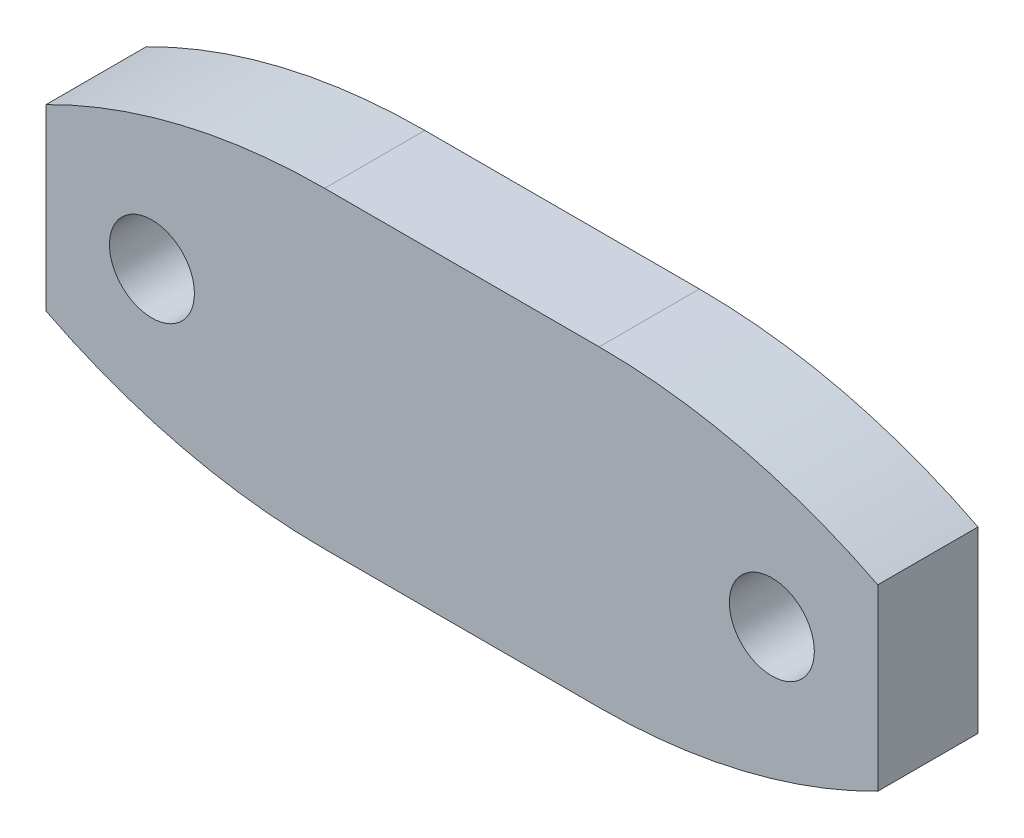
SolidWorks part; units mm, degrees
ref_plane "Front Plane" through (0, 0, 0) normal (0, 0, 1) x (1, 0, 0)
ref_plane "Top Plane" through (0, 0, 0) normal (0, 1, 0) x (1, 0, 0)
ref_plane "Right Plane" through (0, 0, 0) normal (1, 0, 0) x (0, 0, -1)
sketch "Sketch1" plane through (0, 0, 0) normal (0, 0, 1) x (1, 0, 0)
  line L1 (0, 0) -> (63.9, 0)
  line L2 (0, 0) -> (0, 24)
  line L3 (0, 24) -> (63.9, 24)
  line L4 (63.9, 0) -> (63.9, 24)
  dimension "D1" = 63.9
  dimension "D2" = 24
extrude "Boss-Extrude1" add sketch "Sketch1" along normal blind 7.7
sketch "Sketch2" plane through (0, 0, 7.7) normal (0, 0, 1) x (1, 0, 0)
  line L0 (31.95, 12) -> (55.7625, 12) construction
  line L1 (31.95, 24) -> (31.95, 0) construction
  line L2 (63.9, 24) -> (0, 24) construction
  line L3 (0, 0) -> (63.9, 0) construction
  line L4 (31.95, 12) -> (8.1375, 12) construction
  dimension "D1" = 47.625
hole_wizard "5/16-18 Tapped Hole1" positions "3DSketch1" profile "Sketch3" tap size "5/16-18" standard "ANSI Inch" end condition through all
sketch3d "3DSketch1"
  point P0 (8.1375, 12, 7.7)
  point P3 (55.7625, 12, 7.7)
sketch "Sketch3" plane through (8.1375, 12, 7.7) normal (1, 0, 0) x (0, -1, 0)
  line L0 (0, 0) -> (0, 7.7)
  line L1 (0, 7.7) -> (3.2639, 7.7)
  line L2 (3.2639, 7.7) -> (3.2639, 0)
  line L5 (3.2639, 0) -> (0, 0)
  line L11 (0, -6.35) -> (0, 107.95) construction
  dimension "Thru Tap Drill Dia." = 6.5278
  dimension "Thru Tap Drill Depth" = 7.7
cosmetic thread "Hole Thread1" parameters "D2"=7.9375
cosmetic thread "Hole Thread2" parameters "D2"=7.9375
sketch "Sketch4" plane through (0, 0, 7.7) normal (0, 0, 1) x (1, 0, 0)
  line L0 (63.9, 24) -> (63.9, 18.8676)
  line L1 (0, 24) -> (0, 0) construction
  line L2 (31.95, 12) -> (8.1375, 12) construction
  line L3 (31.95, 12) -> (55.7625, 12) construction
  line L4 (31.95, 24) -> (31.95, 0) construction
  line L5 (31.95, 12) -> (8.1375, 12) construction
  line L6 (31.95, 12) -> (55.7625, 12) construction
  line L7 (31.95, 24) -> (31.95, 0) construction
  line L12 (21.4029, 24) -> (0, 24)
  line L14 (63.9, 18.8676) -> (63.9, 24)
  line L16 (0, 24) -> (0, 0)
  line L17 (0, 0) -> (63.9, 0)
  line L18 (63.9, 0) -> (63.9, 24)
  line L19 (63.9, 24) -> (0, 24)
  line L20 (0, 24) -> (0, 18.8676)
  line L24 (63.9, 24) -> (0, 24) construction
  line L25 (42.4971, 24) -> (63.9, 24)
  line L26 (42.4971, 0) -> (63.9, 0)
  line L27 (0, 0) -> (0, 5.1324)
  line L28 (63.9, 5.1324) -> (63.9, 0)
  line L29 (21.4029, 0) -> (0, 0)
  line L30 (63.9, 0) -> (63.9, 5.1324)
  arc A0 (21.4029, 24) -> (0, 18.8676) centre (21.4029, -23.1928) ccw
  arc A1 (42.4971, 24) -> (63.9, 18.8676) centre (42.4971, -23.1928) cw
  arc A2 (42.4971, 0) -> (63.9, 5.1324) centre (42.4971, 47.1928) ccw
  arc A3 (21.4029, 0) -> (0, 5.1324) centre (21.4029, 47.1928) cw
  line M6 (0, 24) -> (0, 0)
  line M7 (0, 0) -> (63.9, 0)
  line M8 (63.9, 0) -> (63.9, 24)
  line M9 (63.9, 24) -> (0, 24)
  dimension "D1" = 0
extrude "Cut-Extrude1" cut sketch "Sketch4" against normal through all contours A0 M9 M6 | A3 M7 M6 | A2 M7 M8 | A1 M9 M8
